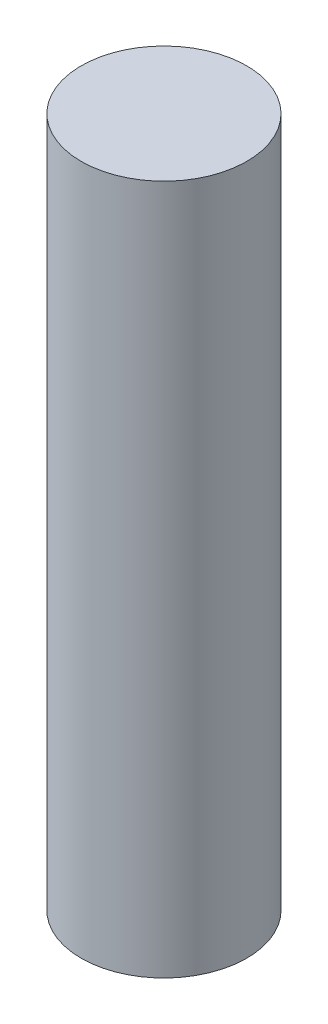
SolidWorks part; units mm, degrees
ref_plane "Front Plane" through (0, 0, 0) normal (0, 0, 1) x (1, 0, 0)
ref_plane "Top Plane" through (0, 0, 0) normal (0, 1, 0) x (1, 0, 0)
ref_plane "Right Plane" through (0, 0, 0) normal (1, 0, 0) x (0, 0, -1)
sketch "Sketch1" plane through (0, 0, 0) normal (0, 1, 0) x (1, 0, 0)
  circle A0 centre (0, 0) radius 1.5
  dimension "D1" = 3
extrude "Boss-Extrude1" add sketch "Sketch1" along normal blind 12.5
sketch "Sketch2" plane through (0, 12.5, 0) normal (0, 1, 0) x (1, 0, 0)
  circle A0 centre (0, 0) radius 2.5
  dimension "D1" = 5
